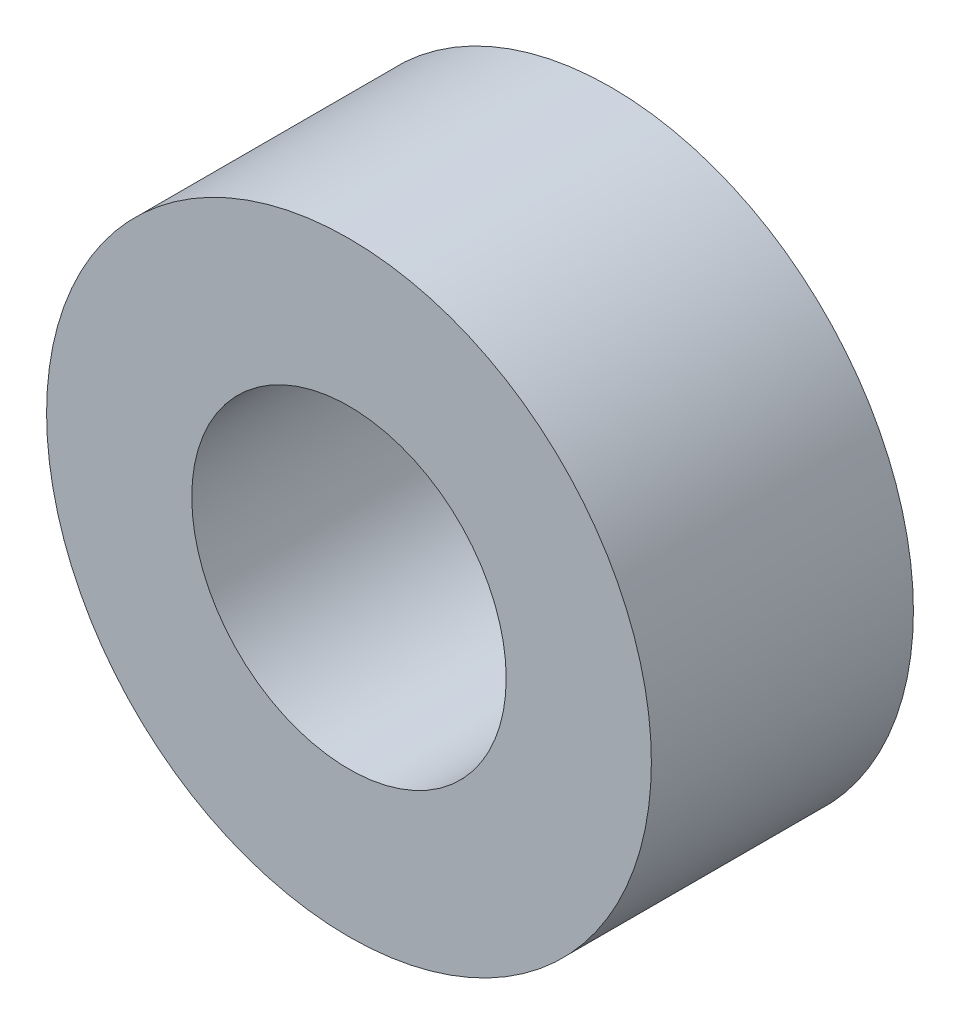
SolidWorks part; units mm, degrees
ref_plane "前视基准面" through (0, 0, 0) normal (0, 0, 1) x (1, 0, 0)
ref_plane "上视基准面" through (0, 0, 0) normal (0, 1, 0) x (1, 0, 0)
ref_plane "右视基准面" through (0, 0, 0) normal (1, 0, 0) x (0, 0, -1)
other "Configuration Table"
sketch "草图1" plane through (0, 0, 0) normal (0, 0, 1) x (1, 0, 0)
  circle A0 centre (0, 0) radius 5.77
extrude "凸台-拉伸1" add sketch "草图1" along normal blind 5
sketch "草图2" plane through (0, 0, 0) normal (0, 0, -1) x (-1, 0, 0)
  circle A0 centre (0, 0) radius 3
extrude "切除-拉伸1" cut sketch "草图2" against normal blind 6
